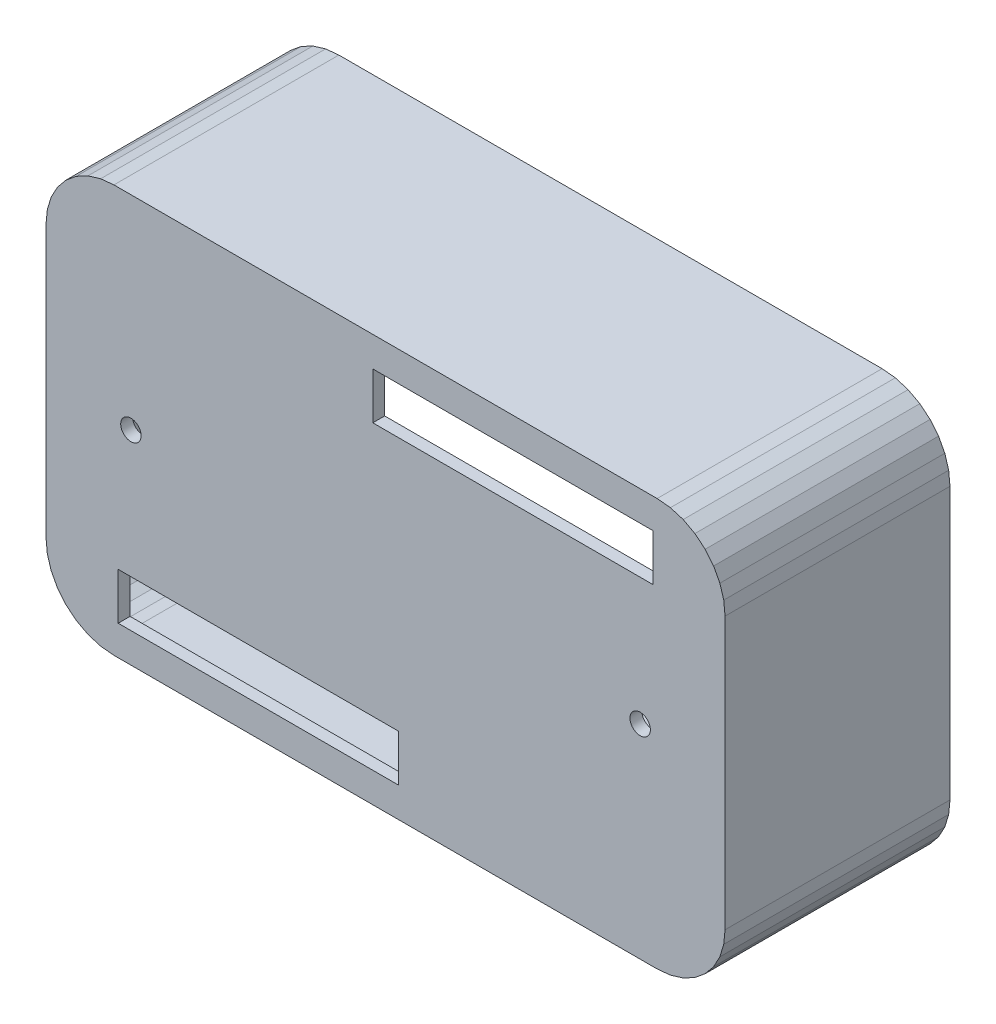
SolidWorks part; units mm, degrees
ref_plane "Front Plane" through (0, 0, 0) normal (0, 0, 1) x (1, 0, 0)
ref_plane "Top Plane" through (0, 0, 0) normal (0, 1, 0) x (1, 0, 0)
ref_plane "Right Plane" through (0, 0, 0) normal (1, 0, 0) x (0, 0, -1)
sketch "Sketch1" plane through (0, 0, 0) normal (0, 0, 1) x (1, 0, 0)
  line L0 (40, 16) -> (39.8463, 17.5607)
  line L1 (39.8463, 17.5607) -> (39.391, 19.0615)
  line L2 (39.391, 19.0615) -> (38.6518, 20.4446)
  line L3 (38.6518, 20.4446) -> (37.6569, 21.6569)
  line L4 (37.6569, 21.6569) -> (36.4446, 22.6518)
  line L5 (36.4446, 22.6518) -> (35.0615, 23.391)
  line L6 (35.0615, 23.391) -> (33.5607, 23.8463)
  line L7 (33.5607, 23.8463) -> (32, 24)
  line L8 (32, 24) -> (-32, 24)
  line L9 (-32, 24) -> (-33.5607, 23.8463)
  line L10 (-33.5607, 23.8463) -> (-35.0615, 23.391)
  line L11 (-35.0615, 23.391) -> (-36.4446, 22.6518)
  line L12 (-36.4446, 22.6518) -> (-37.6569, 21.6569)
  line L13 (-37.6569, 21.6569) -> (-38.6518, 20.4446)
  line L14 (-38.6518, 20.4446) -> (-39.391, 19.0615)
  line L15 (-39.391, 19.0615) -> (-39.8463, 17.5607)
  line L16 (-39.8463, 17.5607) -> (-40, 16)
  line L17 (-40, 16) -> (-40, -16)
  line L18 (-40, -16) -> (-39.8463, -17.5607)
  line L19 (-39.8463, -17.5607) -> (-39.391, -19.0615)
  line L20 (-39.391, -19.0615) -> (-38.6518, -20.4446)
  line L21 (-38.6518, -20.4446) -> (-37.6569, -21.6569)
  line L22 (-37.6569, -21.6569) -> (-36.4446, -22.6518)
  line L23 (-36.4446, -22.6518) -> (-35.0615, -23.391)
  line L24 (-35.0615, -23.391) -> (-33.5607, -23.8463)
  line L25 (-33.5607, -23.8463) -> (-32, -24)
  line L26 (-32, -24) -> (32, -24)
  line L27 (32, -24) -> (33.5607, -23.8463)
  line L28 (33.5607, -23.8463) -> (35.0615, -23.391)
  line L29 (35.0615, -23.391) -> (36.4446, -22.6518)
  line L30 (36.4446, -22.6518) -> (37.6569, -21.6569)
  line L31 (37.6569, -21.6569) -> (38.6518, -20.4446)
  line L32 (38.6518, -20.4446) -> (39.391, -19.0615)
  line L33 (39.391, -19.0615) -> (39.8463, -17.5607)
  line L34 (39.8463, -17.5607) -> (40, -16)
  line L35 (40, -16) -> (40, 16)
extrude "Boss-Extrude1" add sketch "Sketch1" along normal blind 26.5 from offset 2.5
sketch "Sketch2" plane through (0, 0, 0) normal (0, 0, 1) x (1, 0, 0)
  line L0 (38.4, 16) -> (38.277, 17.2486)
  line L1 (38.277, 17.2486) -> (37.9128, 18.4492)
  line L2 (37.9128, 18.4492) -> (37.3214, 19.5556)
  line L3 (37.3214, 19.5556) -> (36.5255, 20.5255)
  line L4 (36.5255, 20.5255) -> (35.5556, 21.3214)
  line L5 (35.5556, 21.3214) -> (34.4492, 21.9128)
  line L6 (34.4492, 21.9128) -> (33.2486, 22.277)
  line L7 (33.2486, 22.277) -> (32, 22.4)
  line L8 (32, 22.4) -> (-32, 22.4)
  line L9 (-32, 22.4) -> (-33.2486, 22.277)
  line L10 (-33.2486, 22.277) -> (-34.4492, 21.9128)
  line L11 (-34.4492, 21.9128) -> (-35.5556, 21.3214)
  line L12 (-35.5556, 21.3214) -> (-36.5255, 20.5255)
  line L13 (-36.5255, 20.5255) -> (-37.3214, 19.5556)
  line L14 (-37.3214, 19.5556) -> (-37.9128, 18.4492)
  line L15 (-37.9128, 18.4492) -> (-38.277, 17.2486)
  line L16 (-38.277, 17.2486) -> (-38.4, 16)
  line L17 (-38.4, 16) -> (-38.4, -16)
  line L18 (-38.4, -16) -> (-38.277, -17.2486)
  line L19 (-38.277, -17.2486) -> (-37.9128, -18.4492)
  line L20 (-37.9128, -18.4492) -> (-37.3214, -19.5556)
  line L21 (-37.3214, -19.5556) -> (-36.5255, -20.5255)
  line L22 (-36.5255, -20.5255) -> (-35.5556, -21.3214)
  line L23 (-35.5556, -21.3214) -> (-34.4492, -21.9128)
  line L24 (-34.4492, -21.9128) -> (-33.2486, -22.277)
  line L25 (-33.2486, -22.277) -> (-32, -22.4)
  line L26 (-32, -22.4) -> (32, -22.4)
  line L27 (32, -22.4) -> (33.2486, -22.277)
  line L28 (33.2486, -22.277) -> (34.4492, -21.9128)
  line L29 (34.4492, -21.9128) -> (35.5556, -21.3214)
  line L30 (35.5556, -21.3214) -> (36.5255, -20.5255)
  line L31 (36.5255, -20.5255) -> (37.3214, -19.5556)
  line L32 (37.3214, -19.5556) -> (37.9128, -18.4492)
  line L33 (37.9128, -18.4492) -> (38.277, -17.2486)
  line L34 (38.277, -17.2486) -> (38.4, -16)
  line L35 (38.4, -16) -> (38.4, 16)
extrude "Cut-Extrude1" cut sketch "Sketch2" along normal blind 25.6 from offset 3
sketch "Sketch3" plane through (0, 0, 0) normal (0, 0, 1) x (1, 0, 0)
  line L0 (-1.5, 14.975) -> (31.5, 14.975)
  line L1 (31.5, 14.975) -> (31.5, 20.475)
  line L2 (31.5, 20.475) -> (-1.5, 20.475)
  line L3 (-1.5, 20.475) -> (-1.5, 14.975)
  line L4 (-31.5, -20.475) -> (1.5, -20.475)
  line L5 (1.5, -20.475) -> (1.5, -14.975)
  line L6 (1.5, -14.975) -> (-31.5, -14.975)
  line L7 (-31.5, -14.975) -> (-31.5, -20.475)
extrude "Cut-Extrude2" cut sketch "Sketch3" against normal through all and the other way through all
sketch "Sketch4" plane through (0, 0, 0) normal (0, 0, 1) x (1, 0, 0)
  circle A0 centre (30, 0) radius 1.2
  circle A1 centre (-30, 0) radius 1.2
extrude "Cut-Extrude3" cut sketch "Sketch4" against normal through all and the other way through all
